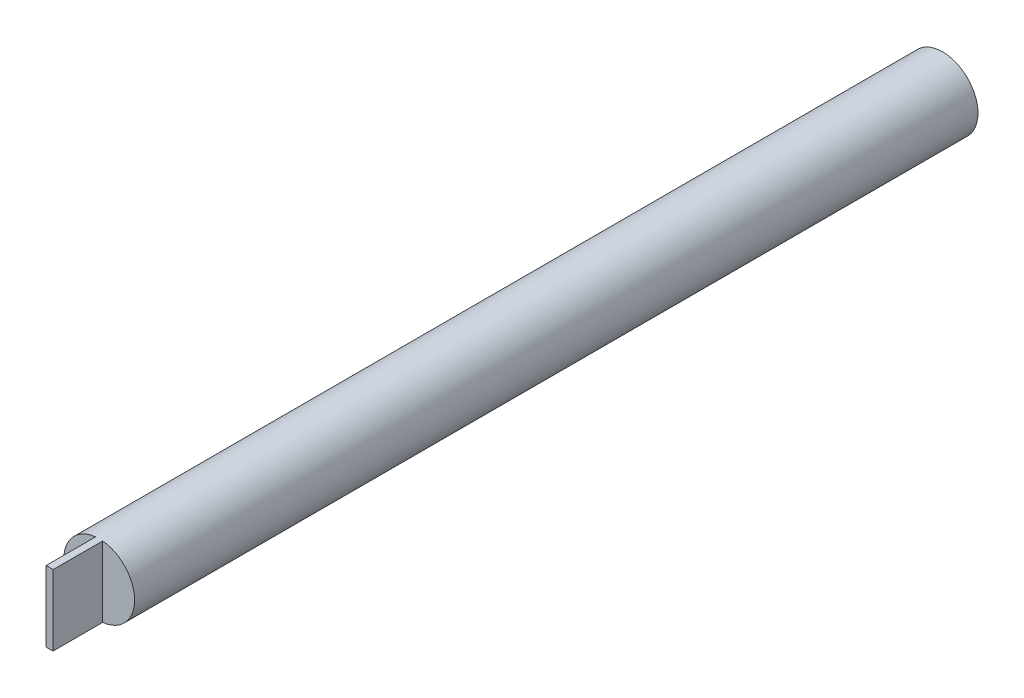
SolidWorks part; units mm, degrees
material "AISI 1020"
ref_plane "Plano frontal" through (0, 0, 0) normal (0, 0, 1) x (1, 0, 0)
ref_plane "Plano superior" through (0, 0, 0) normal (0, 1, 0) x (1, 0, 0)
ref_plane "Plano direito" through (0, 0, 0) normal (1, 0, 0) x (0, 0, -1)
sketch "Esboço1" plane through (0, 0, 0) normal (0, 0, 1) x (1, 0, 0)
  circle A0 centre (0, 100) radius 5
  dimension "D1" = 10
extrude "Ressalto-extrusão1" add sketch "Esboço1" along normal mid plane 126
sketch "Sketch1" plane through (0, 0, 63) normal (0, 0, 1) x (1, 0, 0)
  line L0 (0, 105) -> (0, 95) construction
  line L5 (0.5, 107) -> (0.5, 93)
  line L6 (-5.5, 107) -> (-0.5, 107)
  line L7 (-5.5, 107) -> (-5.5, 93)
  line L8 (-5.5, 93) -> (-0.5, 93)
  line L9 (-0.5, 107) -> (-0.5, 93)
  line L10 (5.5, 93) -> (0.5, 93)
  line L11 (5.5, 107) -> (5.5, 93)
  line L12 (5.5, 107) -> (0.5, 107)
  circle A0 centre (0, 100) radius 5 construction
  point P9 (0, 100)
  dimension "D1" = 5
  dimension "D2" = 14
  dimension "D3" = 0.5
  dimension "D4" = 7
extrude "Cut-Extrude1" cut sketch "Sketch1" against normal blind 7
